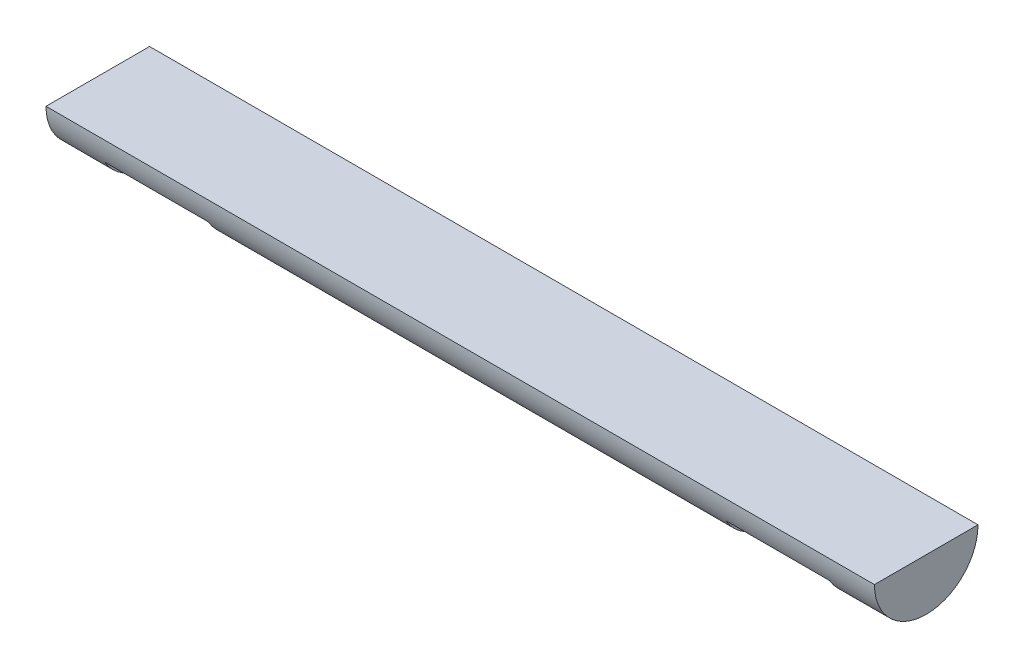
SolidWorks part; units mm, degrees
ref_plane "Front Plane" through (0, 0, 0) normal (0, 0, 1) x (1, 0, 0)
ref_plane "Top Plane" through (0, 0, 0) normal (0, 1, 0) x (1, 0, 0)
ref_plane "Right Plane" through (0, 0, 0) normal (1, 0, 0) x (0, 0, -1)
sketch "Sketch1" plane through (0, 0, 0) normal (1, 0, 0) x (0, 0, -1)
  line L0 (152.4, 0) -> (-152.4, 0)
  arc A0 (-152.4, 0) -> (152.4, 0) centre (0, 0) ccw
  point P4 (0, 0)
  dimension "D1" = 304.8
extrude "Base" add sketch "Sketch1" along normal blind 2743.2
sketch "Sketch2" plane through (0, 0, 0) normal (0, 0, 1) x (1, 0, 0)
  line L0 (304.8, -152.4) -> (304.8, -76.2)
  line L1 (0, -152.4) -> (2743.2, -152.4) construction
  line L2 (304.8, -76.2) -> (609.6, -76.2)
  line L3 (609.6, -76.2) -> (609.6, -152.4)
  line L4 (609.6, -152.4) -> (304.8, -152.4)
  line L5 (0, 0) -> (0, -152.4) construction
  dimension "D1" = 304.8
  dimension "D2" = 304.8
  dimension "D3" = 76.2
extrude "Left Slot" cut sketch "Sketch2" against normal through all both and the other way through all
ref_plane "Midplane" through (1371.6, 0, 0) normal (1, 0, 0) x (0, 0, -1)
mirror "Right Slot" about plane through (1371.6, 0, 0) normal (1, 0, 0) of "Left Slot"
sketch "Sketch3" plane through (0, 0, 0) normal (-1, 0, 0) x (0, 0, 1)
  line L1 (152.4, 0) -> (-152.4, 0)
  line L2 (152.4, 0) -> (-152.4, 0)
  arc A1 (-152.4, 0) -> (152.4, 0) centre (0, 0) ccw
  arc A2 (-152.4, 0) -> (152.4, 0) centre (0, 0) ccw
  dimension "D1" = 0
extrude "Left Cut" cut sketch "Sketch3" against normal blind 152.4
mirror "Right Cut" about plane through (1371.6, 0, 0) normal (1, 0, 0) of "Left Cut"
